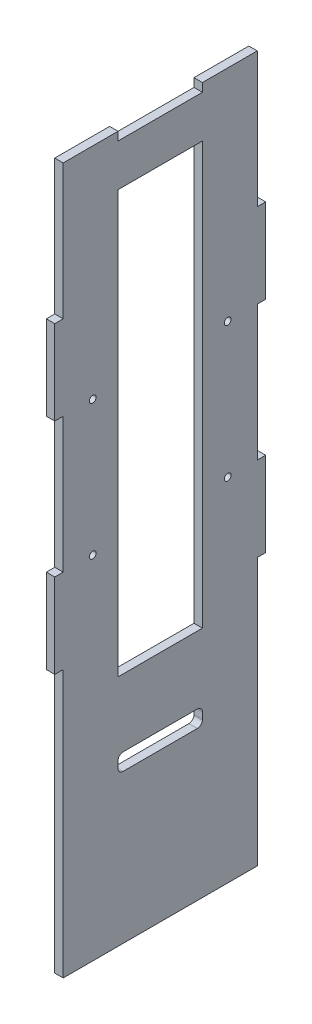
SolidWorks part; units mm, degrees
ref_plane "前视基准面" through (0, 0, 0) normal (0, 0, 1) x (1, 0, 0)
ref_plane "上视基准面" through (0, 0, 0) normal (0, 1, 0) x (1, 0, 0)
ref_plane "右视基准面" through (0, 0, 0) normal (1, 0, 0) x (0, 0, -1)
sketch "草图1" plane through (0, 0, 0) normal (1, 0, 0) x (0, 0, -1)
  line L0 (-115, 195) -> (-115, 275)
  line L1 (-115, -117.3) -> (-115, -143.3)
  line L2 (0, 0) -> (0, 14.9969)
  line L3 (0, 275) -> (-32.5, 275)
  line L4 (-115, 0) -> (-115, 15)
  line L5 (-115, 15) -> (-120, 15)
  line L6 (-82.5, 275) -> (-115, 275)
  line L7 (-115, 65) -> (-120, 65)
  line L8 (-120, 15) -> (-120, 65)
  line L9 (-115, 145) -> (-120, 145)
  line L10 (0, 195) -> (0, 275)
  line L11 (-115, 195) -> (-120, 195)
  line L12 (-120, 145) -> (-120, 195)
  line L13 (0, 195) -> (5, 195)
  line L14 (0, 64.9969) -> (0, 144.9969)
  line L15 (0, 144.9969) -> (5, 144.9969)
  line L16 (5, 195) -> (5, 144.9969)
  line L17 (0, 64.9969) -> (5, 64.9969)
  line L18 (-115, 65) -> (-115, 145)
  line L19 (0, 14.9969) -> (5, 14.9969)
  line L20 (5, 64.9969) -> (5, 14.9969)
  line L21 (-115, 0) -> (-115, -117.3)
  line L22 (-82.5, 275) -> (-82.5, 270)
  line L23 (-82.5, 270) -> (-32.5, 270)
  line L24 (-32.5, 275) -> (-32.5, 270)
  line L25 (-82.5, 245) -> (-32.5, 245)
  line L26 (-82.5, 245) -> (-82.5, -5)
  line L27 (-82.5, -5) -> (-32.5, -5)
  line L28 (-32.5, 245) -> (-32.5, -5)
  line L29 (-97.5, 302.936) -> (-97.5, -157.8768) construction
  line L30 (0, -117.3) -> (0, 0)
  line L31 (-115, -143.3) -> (0, -143.3)
  line L32 (0, -143.3) -> (0, -117.3)
  line L33 (-79.5, -45) -> (-35.5, -45)
  line L34 (-82.5, -48) -> (-82.5, -52)
  line L35 (-79.5, -55) -> (-35.5, -55)
  line L36 (-32.5, -48) -> (-32.5, -52)
  line L37 (-17.5, -157.8768) -> (-17.5, 302.936) construction
  line L38 (-195.5225, 144.9969) -> (145.3444, 144.9969) construction
  line L39 (-200.4183, 64.9969) -> (145.3444, 64.9969) construction
  arc A0 (-35.5, -45) -> (-32.5, -48) centre (-35.5, -48) cw
  arc A1 (-35.5, -55) -> (-32.5, -52) centre (-35.5, -52) ccw
  arc A2 (-82.5, -52) -> (-79.5, -55) centre (-79.5, -52) ccw
  arc A3 (-79.5, -45) -> (-82.5, -48) centre (-79.5, -48) ccw
  circle A4 centre (-97.5, 145) radius 2
  circle A5 centre (-17.5, 144.9969) radius 2
  circle A6 centre (-17.5, 64.9969) radius 2
  circle A7 centre (-97.5, 64.9969) radius 2
  dimension "D23" = 3
  dimension "D1" = 115
  dimension "D2" = 275
  dimension "D3" = 5
  dimension "D4" = 5
  dimension "D5" = 5
  dimension "D6" = 5
  dimension "D7" = 5
  dimension "D8" = 50
  dimension "D9" = 50
  dimension "D10" = 50.0031
  dimension "D11" = 50
  dimension "D12" = 50
  dimension "D13" = 80
  dimension "D14" = 80
  dimension "D15" = 80
  dimension "D16" = 80
  dimension "D17" = 50
  dimension "D18" = 32.5
  dimension "D19" = 32.5
  dimension "D20" = 40
  dimension "D21" = 30
  dimension "D22" = 32.5
  dimension "D24" = 115
  dimension "D25" = 80
  dimension "D26" = 15
  dimension "D27" = 80
  dimension "D28" = 0
extrude "凸台-拉伸1" add sketch "草图1" along normal blind 5
